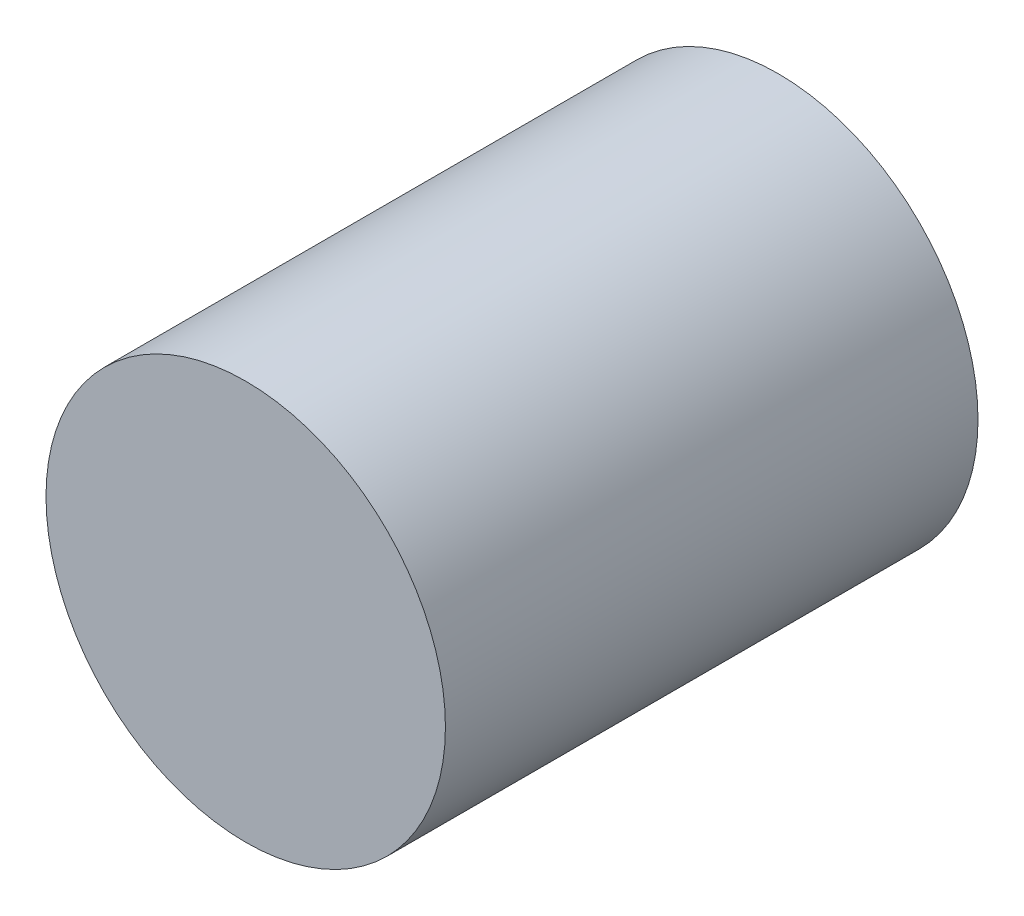
SolidWorks part; units mm, degrees
material "6061-T6 (SS)"
ref_plane "Front Plane" through (0, 0, 0) normal (0, 0, 1) x (1, 0, 0)
ref_plane "Top Plane" through (0, 0, 0) normal (0, 1, 0) x (1, 0, 0)
ref_plane "Right Plane" through (0, 0, 0) normal (1, 0, 0) x (0, 0, -1)
sketch "Sketch1" plane through (0, 0, 0) normal (0, 0, 1) x (1, 0, 0)
  circle A0 centre (0, 0) radius 9.525
  dimension "D1" = 19.05
extrude "Extrude1" add sketch "Sketch1" along normal mid plane 25.4
